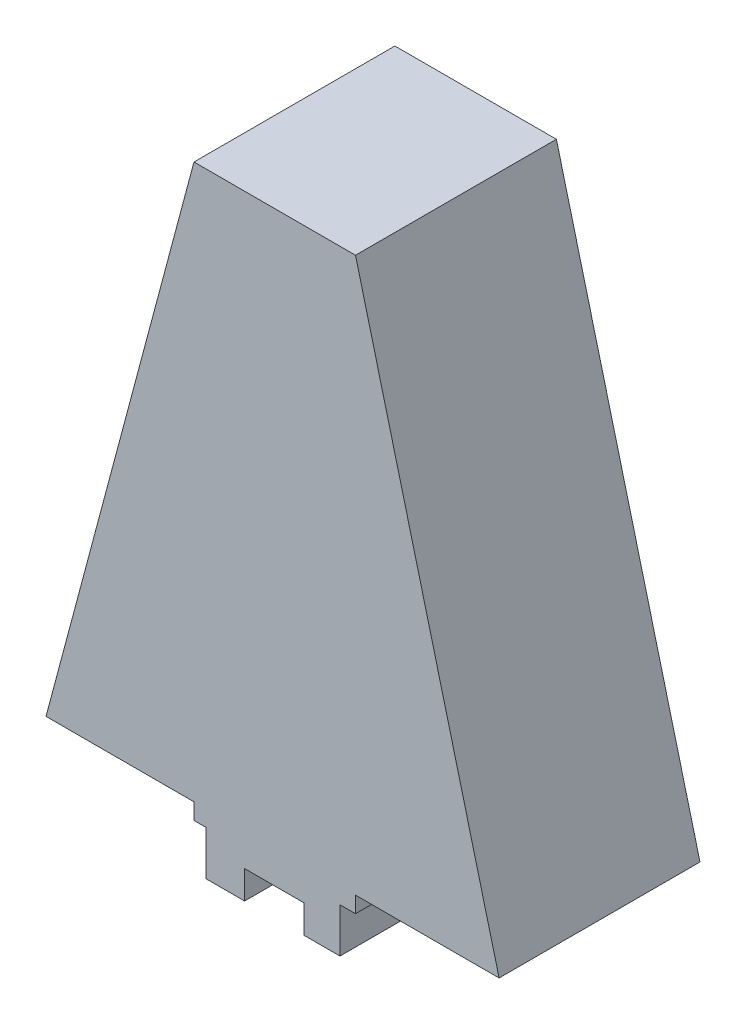
SolidWorks part; units mm, degrees
ref_plane "Front Plane" through (0, 0, 0) normal (0, 0, 1) x (1, 0, 0)
ref_plane "Top Plane" through (0, 0, 0) normal (0, 1, 0) x (1, 0, 0)
ref_plane "Right Plane" through (0, 0, 0) normal (1, 0, 0) x (0, 0, -1)
sketch "Sketch1" plane through (0, 0, 0) normal (0, 0, 1) x (1, 0, 0)
  line L0 (0.0082, -0.071) -> (0.0101, -0.071)
  line L1 (-0.01, 0) -> (0.0101, 0)
  line L2 (-0.01, -0.069) -> (-0.01, -0.071)
  line L3 (-0.01, -0.071) -> (-0.0085, -0.071)
  line L4 (0.0101, -0.069) -> (0.0101, -0.071)
  line L5 (-0.0085, -0.0765) -> (-0.0037, -0.0765)
  line L6 (-0.0085, -0.0765) -> (-0.0085, -0.073)
  line L8 (-0.0037, -0.0765) -> (-0.0037, -0.073)
  line L9 (0.0037, -0.0765) -> (0.0082, -0.0765)
  line L10 (0.0037, -0.0765) -> (0.0037, -0.073)
  line L12 (0.0082, -0.0765) -> (0.0082, -0.073)
  line L13 (-0.0037, -0.073) -> (0.0037, -0.073)
  line L14 (-0.0085, -0.073) -> (-0.0085, -0.071)
  line L16 (0.0082, -0.073) -> (0.0082, -0.071)
  line L17 (-0.01, -0.069) -> (-0.0284, -0.069)
  line L18 (-0.0284, -0.069) -> (-0.01, 0)
  line L19 (0.0101, -0.069) -> (0.028, -0.069)
  line L20 (0.028, -0.069) -> (0.0101, 0)
  point P4 (0, 0)
  point P22 (0, 0)
  point P23 (0, 0)
  point P24 (0, 0)
  point P25 (0, 0)
  point P26 (0, 0)
  point P27 (0, 0)
  point P28 (0, 0)
extrude "Boss-Extrude1" add sketch "Sketch1" along normal blind 0.025
equation "\"10.00000umm\"=10"
